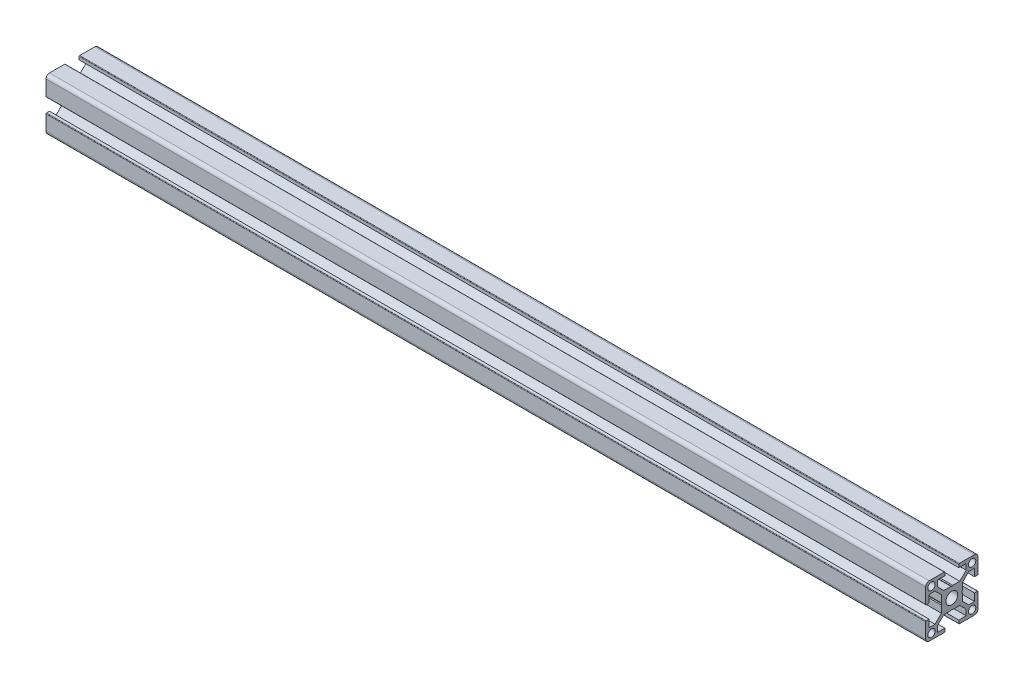
SolidWorks part; units mm, degrees
ref_plane "Front Plane" through (0, 0, 0) normal (0, 0, 1) x (1, 0, 0)
ref_plane "Top Plane" through (0, 0, 0) normal (0, 1, 0) x (1, 0, 0)
ref_plane "Right Plane" through (0, 0, 0) normal (1, 0, 0) x (0, 0, -1)
sketch "Sketch1" plane through (0, 0, 0) normal (0, 0, 1) x (1, 0, 0)
  line L0 (0, 0) -> (504, 0)
  dimension "D1" = 504
other "30xs6 30X30S6(1)"
ref_plane "Plane1" through (0, 0, 0) normal (1, 0, 0) x (0, 1, 0)
sketch "草图1" plane through (0, 0, 0) normal (1, 0, 0) x (0, 1, 0)
  line L0 (-14.7, 4) -> (-13, 4)
  line L1 (-13, 4) -> (-13, 8.25)
  line L2 (-13, 8.25) -> (-9.6642, 8.25)
  line L3 (-9.6642, 8.25) -> (-6, 4.5858)
  line L4 (-6, 4.5858) -> (-6, 0.5196)
  line L5 (-6, 0.5196) -> (-5.7, 0)
  line L6 (-5.7, 0) -> (-6, -0.5196)
  line L7 (-6, -0.5196) -> (-6, -4.5858)
  line L8 (-6, -4.5858) -> (-9.6642, -8.25)
  line L9 (-9.6642, -8.25) -> (-13, -8.25)
  line L10 (-13, -8.25) -> (-13, -4)
  line L11 (-13, -4) -> (-14.7, -4)
  line L12 (-15, -4.3) -> (-15, -13)
  line L13 (-13, -15) -> (-4.3, -15)
  line L14 (-4, -14.7) -> (-4, -13)
  line L15 (-4, -13) -> (-8.25, -13)
  line L16 (-8.25, -13) -> (-8.25, -9.6642)
  line L17 (-8.25, -9.6642) -> (-4.5858, -6)
  line L18 (-4.5858, -6) -> (-0.5196, -6)
  line L19 (-0.5196, -6) -> (0, -5.7)
  line L20 (0, -5.7) -> (0.5196, -6)
  line L21 (0.5196, -6) -> (4.5858, -6)
  line L22 (4.5858, -6) -> (8.25, -9.6642)
  line L23 (8.25, -9.6642) -> (8.25, -13)
  line L24 (8.25, -13) -> (4, -13)
  line L25 (4, -13) -> (4, -14.7)
  line L26 (4.3, -15) -> (13, -15)
  line L27 (15, -13) -> (15, -4.3)
  line L28 (14.7, -4) -> (13, -4)
  line L29 (13, -4) -> (13, -8.25)
  line L30 (13, -8.25) -> (9.6642, -8.25)
  line L31 (9.6642, -8.25) -> (6, -4.5858)
  line L32 (6, -4.5858) -> (6, -0.5196)
  line L33 (6, -0.5196) -> (5.7, 0)
  line L34 (5.7, 0) -> (6, 0.5196)
  line L35 (6, 0.5196) -> (6, 4.5858)
  line L36 (6, 4.5858) -> (9.6642, 8.25)
  line L37 (9.6642, 8.25) -> (13, 8.25)
  line L38 (13, 8.25) -> (13, 4)
  line L39 (13, 4) -> (14.7, 4)
  line L40 (15, 4.3) -> (15, 13)
  line L41 (13, 15) -> (4.3, 15)
  line L42 (4, 14.7) -> (4, 13)
  line L43 (4, 13) -> (8.25, 13)
  line L44 (8.25, 13) -> (8.25, 9.6642)
  line L45 (8.25, 9.6642) -> (4.5858, 6)
  line L46 (4.5858, 6) -> (0.5196, 6)
  line L47 (0.5196, 6) -> (0, 5.7)
  line L48 (0, 5.7) -> (-0.5196, 6)
  line L49 (-0.5196, 6) -> (-4.5858, 6)
  line L50 (-4.5858, 6) -> (-8.25, 9.6642)
  line L51 (-8.25, 9.6642) -> (-8.25, 13)
  line L52 (-8.25, 13) -> (-4, 13)
  line L53 (-4, 13) -> (-4, 14.7)
  line L54 (-4.3, 15) -> (-13, 15)
  line L55 (-15, 13) -> (-15, 4.3)
  arc A0 (-15, 4.3) -> (-14.7, 4) centre (-14.7, 4.3) ccw
  arc A1 (-14.7, -4) -> (-15, -4.3) centre (-14.7, -4.3) ccw
  arc A2 (-15, -13) -> (-13, -15) centre (-13, -13) ccw
  arc A3 (-4.3, -15) -> (-4, -14.7) centre (-4.3, -14.7) ccw
  arc A4 (4, -14.7) -> (4.3, -15) centre (4.3, -14.7) ccw
  arc A5 (13, -15) -> (15, -13) centre (13, -13) ccw
  arc A6 (15, -4.3) -> (14.7, -4) centre (14.7, -4.3) ccw
  arc A7 (14.7, 4) -> (15, 4.3) centre (14.7, 4.3) ccw
  arc A8 (15, 13) -> (13, 15) centre (13, 13) ccw
  arc A9 (4.3, 15) -> (4, 14.7) centre (4.3, 14.7) ccw
  arc A10 (-4, 14.7) -> (-4.3, 15) centre (-4.3, 14.7) ccw
  arc A11 (-13, 15) -> (-15, 13) centre (-13, 13) ccw
  circle A12 centre (11.625, 11.625) radius 2.1
  circle A13 centre (11.625, -11.625) radius 2.1
  circle A14 centre (0, 0) radius 3.4
  circle A15 centre (-11.625, -11.625) radius 2.1
  circle A16 centre (-11.625, 11.625) radius 2.1
  point P90 (-15, 15)
  point P91 (-0.2598, 14.9121)
  point P92 (15, 15)
  point P93 (15, 0)
  point P94 (15, -15)
  point P95 (0.2598, -15)
  point P96 (-15, -15)
  point P97 (-15, 0)
  point P98 (0, 0)
